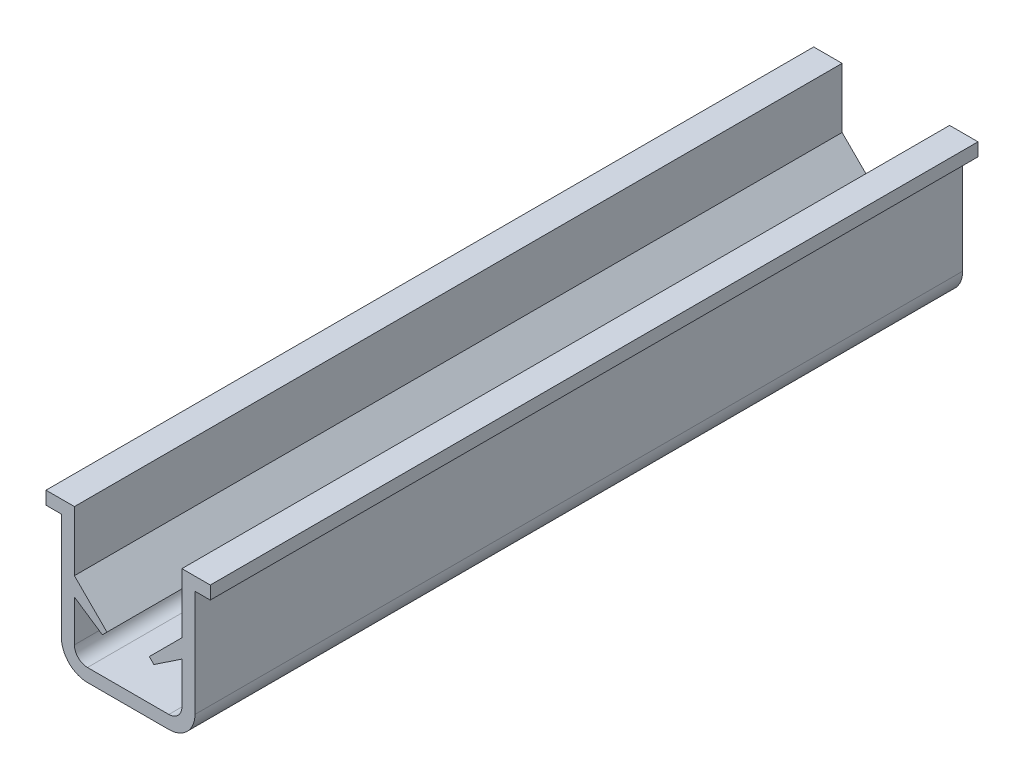
SolidWorks part; units mm, degrees
ref_plane "前视基准面" through (0, 0, 0) normal (0, 0, 1) x (1, 0, 0)
ref_plane "上视基准面" through (0, 0, 0) normal (0, 1, 0) x (1, 0, 0)
ref_plane "右视基准面" through (0, 0, 0) normal (1, 0, 0) x (0, 0, -1)
sketch "草图1" plane through (0, 0, 0) normal (0, 0, 1) x (1, 0, 0)
  line L0 (-3.0687, 0.0753) -> (-3.0687, 3.9753)
  line L1 (-3.0687, 3.9753) -> (-4.9187, 3.9753)
  line L2 (-4.9187, 3.9753) -> (-4.9187, 3.1253)
  line L3 (-4.9187, 3.1253) -> (-3.9187, 3.1253)
  line L4 (-3.9187, 3.1253) -> (-3.9187, -3.8247)
  line L5 (-2.2187, -5.5247) -> (3.0813, -5.5247)
  line L6 (4.7813, -3.8247) -> (4.7813, 3.1253)
  line L7 (4.7813, 3.1253) -> (5.7813, 3.1253)
  line L8 (5.7813, 3.1253) -> (5.7813, 3.9753)
  line L9 (5.7813, 3.9753) -> (3.9313, 3.9753)
  line L10 (3.9313, 3.9753) -> (3.9313, 0.0753)
  line L11 (3.9313, 0.0753) -> (1.81, -2.046)
  line L12 (1.81, -2.046) -> (2.1105, -2.3465)
  line L13 (2.1105, -2.3465) -> (3.9313, -1.1268)
  line L14 (3.9313, -1.1268) -> (3.9313, -3.8247)
  line L15 (3.0813, -4.6747) -> (-2.2187, -4.6747)
  line L16 (-3.0687, -3.8247) -> (-3.0687, -1.1268)
  line L17 (-3.0687, -1.1268) -> (-1.2479, -2.3465)
  line L18 (-1.2479, -2.3465) -> (-0.9474, -2.046)
  line L19 (-0.9474, -2.046) -> (-3.0687, 0.0753)
  arc A0 (-3.9187, -3.8247) -> (-2.2187, -5.5247) centre (-2.2187, -3.8247) ccw
  arc A1 (3.0813, -5.5247) -> (4.7813, -3.8247) centre (3.0813, -3.8247) ccw
  arc A2 (3.0813, -4.6747) -> (3.9313, -3.8247) centre (3.0813, -3.8247) ccw
  arc A3 (-3.0687, -3.8247) -> (-2.2187, -4.6747) centre (-2.2187, -3.8247) ccw
extrude "凸台-拉伸1" add sketch "草图1" along normal blind 50
